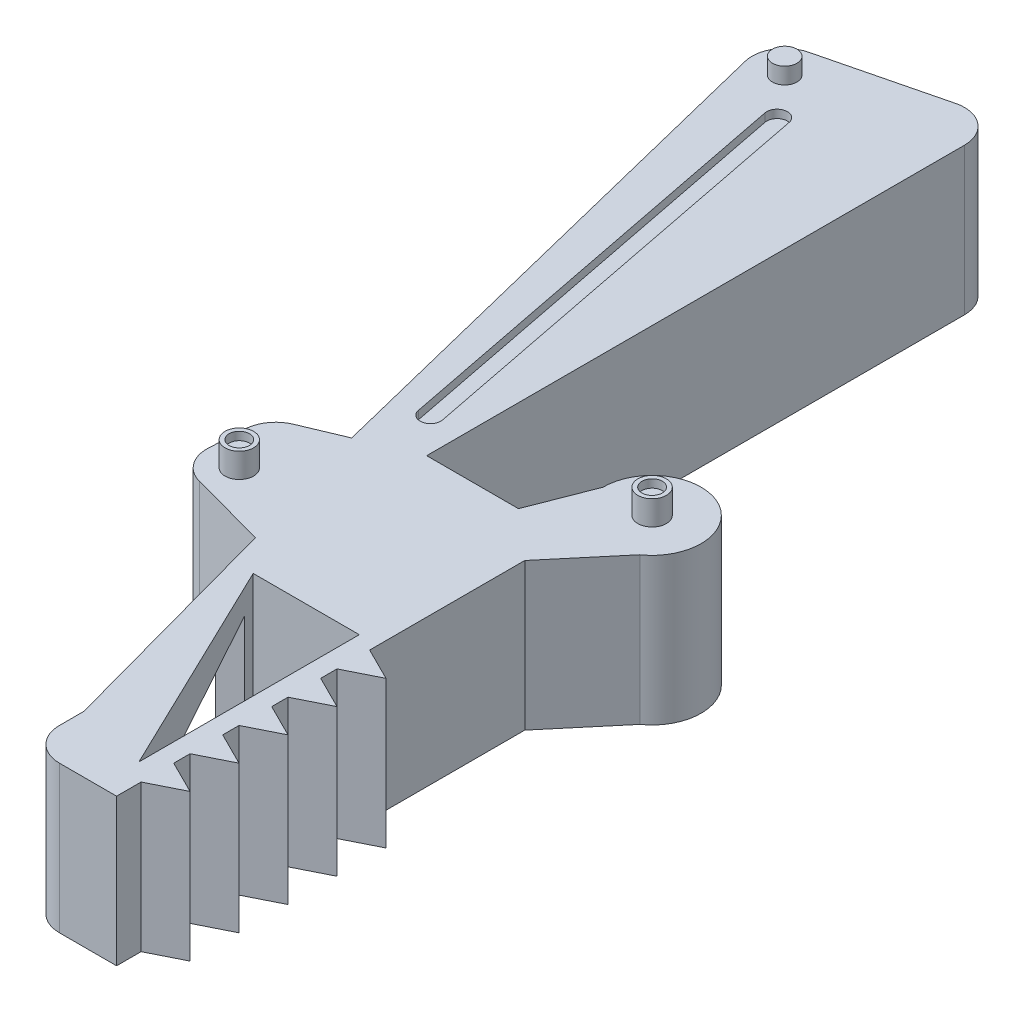
SolidWorks part; units mm, degrees
ref_plane "Front Plane" through (0, 0, 0) normal (0, 0, 1) x (1, 0, 0)
ref_plane "Top Plane" through (0, 0, 0) normal (0, 1, 0) x (1, 0, 0)
ref_plane "Right Plane" through (0, 0, 0) normal (1, 0, 0) x (0, 0, -1)
sketch "Sketch1" plane through (0, 0, 0) normal (0, 1, 0) x (1, 0, 0)
  line L0 (0, 0) -> (-64.6704, 0) construction
  line L1 (-34.4961, 0) -> (-57.7927, -5.768)
  line L2 (-57.7927, -5.768) -> (-40.9693, -73.7163)
  line L3 (-40.9693, -73.7163) -> (-34.4961, -71)
  line L4 (-34.4961, -71) -> (-34.4961, 0)
  line L5 (-34.4961, -71) -> (-48.3277, -76.8041)
  line L6 (-48.3277, -76.8041) -> (-48.8384, -86.7911)
  line L7 (-48.8384, -86.7911) -> (-36.2867, -90.1755)
  line L8 (-36.2867, -90.1755) -> (-28.3697, -119.112)
  line L9 (-28.3697, -119.112) -> (-28.3697, -126.112)
  line L10 (-28.3697, -126.112) -> (-17.3697, -126.112)
  line L11 (-17.3697, -126.112) -> (-17.3697, -76.112)
  line L12 (-17.3697, -76.112) -> (-10.9363, -68.4562)
  line L13 (-34.4961, -71) -> (-23.248, -71)
  line L14 (-23.248, -71) -> (-20.3555, -63.5654)
  arc A0 (-20.3555, -63.5654) -> (-10.9363, -68.4562) centre (-14.3556, -63.5258) cw
  dimension "D4" = 6
  dimension "D1" = 24
  dimension "D2" = 70
  dimension "D3" = 71
  dimension "D5" = 10
  dimension "D6" = 13
  dimension "D7" = 30
  dimension "D8" = 7
  dimension "D9" = 11
  dimension "D10" = 50
  dimension "D11" = 10
  dimension "D12" = 15
  dimension "D13" = 63.5258
  dimension "D14" = 5.768
extrude "Boss-Extrude1" add sketch "Sketch1" along normal blind 18 contours L3 L4 L1 L2 | A0 L14 L13 L3 L5 L6 L7 L8 L9 L10 L11 L12
fillet "Fillet2" radius 4 5 edges at (-28.3697, 9, 126.112) (-48.8384, 9, 86.7911) (-48.3277, 9, 76.8041) (-34.4961, 9, 0) (-57.7927, 9, 5.768)
sketch "Sketch2" plane through (0, 18, 0) normal (0, 1, 0) x (1, 0, 0)
  line L0 (-17.3697, -126.112) -> (-17.3697, -121.112) construction
  line L1 (-17.3697, -126.112) -> (-17.3697, -76.112) construction
  line L2 (-17.3697, -119.112) -> (-17.3697, -123.112)
  line L3 (-17.3697, -121.112) -> (-13.3697, -121.112) construction
  line L4 (-17.3697, -119.112) -> (-13.3697, -121.112)
  line L5 (-13.3697, -121.112) -> (-17.3697, -123.112)
  dimension "D1" = 5
  dimension "D2" = 4
  dimension "D3" = 4
  dimension "D4" = 2
extrude "Boss-Extrude2" add sketch "Sketch2" against normal through all
pattern_linear "LPattern1" count 5 spacing 6 along (0, 0, -1) of "Boss-Extrude2"
sketch "Sketch3" plane through (0, 18, 0) normal (0, 1, 0) x (1, 0, 0)
  line L0 (-19.6318, -121.1169) -> (-19.6318, -94.1169)
  line L1 (-19.6318, -94.1169) -> (-32.6318, -94.1169)
  line L2 (-32.6318, -94.1169) -> (-19.6318, -121.1169)
  dimension "D1" = 13
  dimension "D2" = 27
extrude "Cut-Extrude1" cut sketch "Sketch3" against normal blind 26
sketch "Sketch4" plane through (-56.7132, 0, 15.5166) normal (-0.9646, 0, 0.2639) x (0.2639, 0, 0.9646)
  line L0 (84.4028, 15) -> (84.4028, 3)
  line L1 (84.4028, 3) -> (102.4028, 5.4564)
  line L2 (102.4028, 5.4564) -> (102.4028, 12.5436)
  line L3 (102.4028, 12.5436) -> (84.4028, 15)
  line L4 (77.4028, 18) -> (107.4028, 18) construction
  line L5 (77.4028, 0) -> (107.4028, 0) construction
  line L6 (107.4028, 18) -> (107.4028, 0) construction
  line L7 (77.4028, 18) -> (77.4028, 0) construction
  point P13 (107.4028, 9)
  point P14 (102.4028, 9)
  dimension "D1" = 3
  dimension "D2" = 3
  dimension "D3" = 5
  dimension "D4" = 7
extrude "Cut-Extrude2" cut sketch "Sketch4" against normal blind 8
sketch "Sketch5" plane through (0, 18, 0) normal (0, 1, 0) x (1, 0, 0)
  circle A0 centre (-52.9486, -8.6894) radius 1.5
sketch "Sketch6" plane through (0, 18, 0) normal (0, 1, 0) x (1, 0, 0)
  circle A0 centre (-14.3556, -63.5258) radius 1.75
  circle A1 centre (-44.6787, -83.7698) radius 1.75
extrude "Boss-Extrude3" add sketch "Sketch6" along normal blind 3
sketch "Sketch7" plane through (0, 21, 0) normal (0, 1, 0) x (1, 0, 0)
  circle A2 centre (-14.3556, -63.5258) radius 1.25
  circle A3 centre (-14.3556, -63.5258) radius 1.25
  dimension "D1" = 0.5
extrude "Cut-Extrude4" cut sketch "Sketch7" against normal blind 1
sketch "Sketch8" plane through (0, 21, 0) normal (0, 1, 0) x (1, 0, 0)
  circle A2 centre (-44.6787, -83.7698) radius 1.25
  circle A3 centre (-44.6787, -83.7698) radius 1.25
  dimension "D1" = 0.5
extrude "Cut-Extrude5" cut sketch "Sketch8" against normal blind 1
sketch "Sketch9" plane through (0, 18, 0) normal (0, 1, 0) x (1, 0, 0)
  line L0 (-48.8978, -13.6747) -> (-38.5596, -66.473) construction
  line L1 (-47.6532, -13.431) -> (-37.3151, -66.2293)
  line L2 (-50.1423, -13.9184) -> (-39.8042, -66.7167)
  arc A0 (-47.6532, -13.431) -> (-50.1423, -13.9184) centre (-48.8978, -13.6747) ccw
  arc A1 (-39.8042, -66.7167) -> (-37.3151, -66.2293) centre (-38.5596, -66.473) ccw
  point P2 (-43.7287, -40.0738)
extrude "Cut-Extrude6" cut sketch "Sketch9" against normal blind 1
ref_plane "Plane1" through (0, 9, 0) normal (0, 1, 0) x (1, 0, 0)
extrude "Boss-Extrude4" add sketch "Sketch5" along normal blind 2
mirror "Mirror1" about plane through (0, 9, 0) normal (0, 1, 0) of "Boss-Extrude4"
